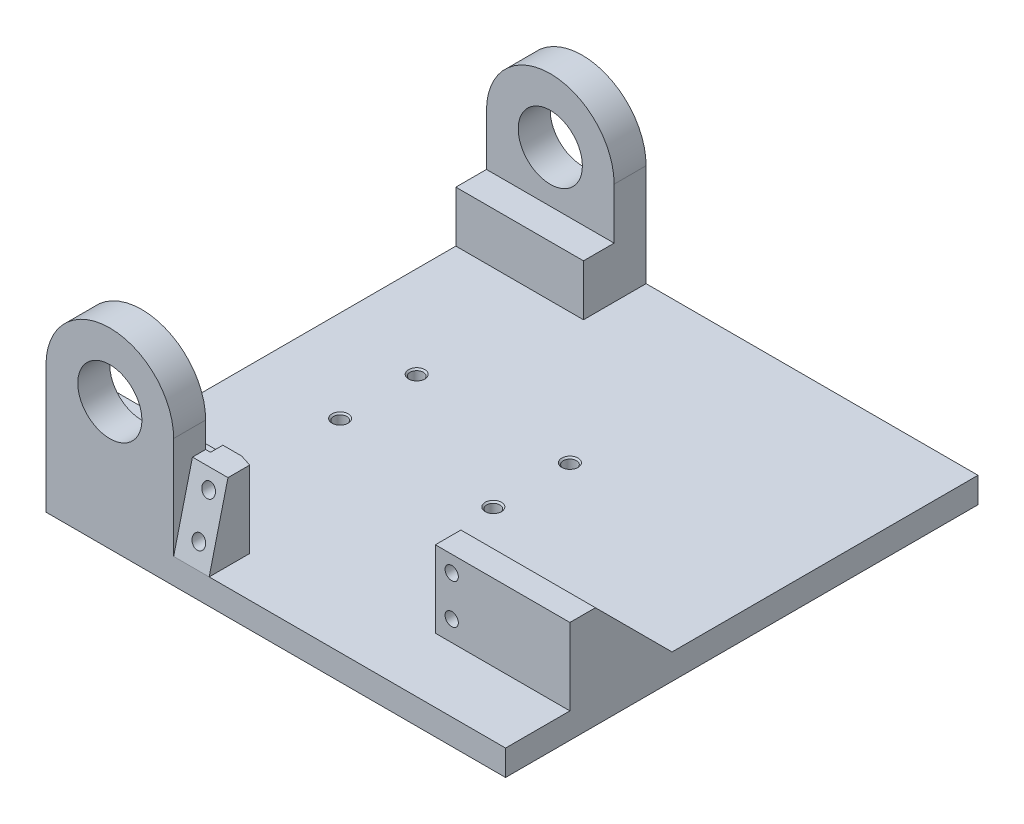
SolidWorks part; units mm, degrees
ref_plane "Front Plane" through (0, 0, 0) normal (0, 0, 1) x (1, 0, 0)
ref_plane "Top Plane" through (0, 0, 0) normal (0, 1, 0) x (1, 0, 0)
ref_plane "Right Plane" through (0, 0, 0) normal (1, 0, 0) x (0, 0, -1)
sketch "Sketch1" plane through (0, 0, 0) normal (0, 0, 1) x (1, 0, 0)
  line L0 (0, 0) -> (0, -38.1) construction
  line L1 (0, 0) -> (-38.1, 0) construction
  line L2 (0, 0) -> (38.1, 0) construction
  circle A0 centre (0, 0) radius 38.1 construction
  dimension "D1" = 76.2
  dimension "D2" = 90
  dimension "D3" = 90
sketch "Sketch2" plane through (0, 0, 0) normal (0, 0, 1) x (1, 0, 0)
  line L0 (0, -38.1) -> (0, 38.1) construction
  line L1 (-22.225, 0) -> (-22.225, -25.4)
  line L4 (-53.975, 0) -> (-53.975, -31.75)
  line L5 (-53.975, -31.75) -> (53.975, -31.75)
  line L9 (53.975, 0) -> (53.975, -31.75) construction
  line L10 (22.225, 0) -> (22.225, -25.4) construction
  line L11 (22.225, -25.4) -> (53.975, -25.4)
  line L12 (53.975, -25.4) -> (53.975, -31.75)
  line L13 (-22.225, -25.4) -> (22.225, -25.4)
  circle A0 centre (-38.1, 0) radius 7.9756
  arc A1 (-22.225, 0) -> (-53.975, 0) centre (-38.1, 0) ccw
  circle A2 centre (0, 0) radius 38.1 construction
  arc A5 (22.225, 0) -> (53.975, 0) centre (38.1, 0) cw construction
  circle A6 centre (38.1, 0) radius 7.9756 construction
  dimension "D1" = 15.9512
  dimension "D2" = 31.75
  dimension "D3" = 6.35
  dimension "D4" = 25.4
extrude "Boss-Extrude1" add sketch "Sketch2" along normal blind 7.9502 contours L1 L13 L12 L5 L4 A1
sketch "Sketch3" plane through (0, 0, 7.9502) normal (0, 0, 1) x (1, 0, 0)
  line L0 (53.975, -31.75) -> (53.975, -25.4) construction
  line L1 (-53.975, -31.75) -> (53.975, -31.75)
  line L2 (-53.975, -31.75) -> (-53.975, -25.4)
  line L3 (-53.975, -25.4) -> (53.975, -25.4)
  line L4 (53.975, -31.75) -> (53.975, -25.4)
  line L5 (53.975, -25.4) -> (-22.225, -25.4) construction
extrude "Boss-Extrude2" add sketch "Sketch3" along normal blind 101.6
sketch "Sketch4" plane through (0, 0, 109.5502) normal (0, 0, 1) x (1, 0, 0)
  line L0 (-53.975, 0) -> (-53.975, -31.75)
  line L1 (-53.975, -31.75) -> (53.975, -31.75)
  line L3 (-22.225, 0) -> (-22.225, -25.4)
  line L6 (-22.225, -25.4) -> (53.975, -25.4)
  line L7 (53.975, -25.4) -> (53.975, -31.75)
  circle A0 centre (-38.1, 0) radius 7.9756
  arc A1 (-22.225, 0) -> (-53.975, 0) centre (-38.1, 0) ccw
  circle A4 centre (-38.1, 0) radius 7.9756 construction
  dimension "D1" = 15.9512
extrude "Boss-Extrude3" add sketch "Sketch4" along normal blind 7.9502
sketch "Sketch5" plane through (53.975, 0, 0) normal (1, 0, 0) x (0, 0, -1)
  line L1 (0, -31.75) -> (-117.5004, -31.75)
  line L2 (0, -31.75) -> (0, -25.4)
  line L3 (0, -25.4) -> (-117.5004, -25.4)
  line L4 (-117.5004, -31.75) -> (-117.5004, -25.4)
extrude "Boss-Extrude4" add sketch "Sketch5" along normal blind 6.35
sketch "Sketch6" plane through (0, -25.4, 0) normal (0, 1, 0) x (1, 0, 0)
  line L0 (60.325, 0) -> (60.325, -117.5004) construction
  line L1 (60.325, -101.4984) -> (26.8617, -101.4984)
  line L2 (60.325, -101.4984) -> (60.325, -95.1484)
  line L3 (60.325, -95.1484) -> (26.8617, -95.1484)
  line L4 (26.8617, -101.4984) -> (26.8617, -95.1484)
  line L5 (26.8617, -102.4002) -> (26.8617, -74.9502) construction
  line L6 (60.325, -117.5004) -> (-22.225, -117.5004) construction
  line L7 (-20.2383, -106.4752) -> (-14.2383, -106.4752) construction
  line L9 (-13.3923, -112.8252) -> (-13.3923, -107.4183)
  line L10 (-16.3298, -106.4752) -> (-21.0123, -106.4752)
  line L12 (-13.1383, -105.5502) -> (-13.1383, -113.7002) construction
  line L13 (-21.0123, -106.4752) -> (-21.0123, -109.5502)
  line L14 (-22.225, -109.5502) -> (-53.975, -109.5502) construction
  line L15 (-21.0123, -109.5502) -> (-22.225, -109.5502)
  line L16 (-22.225, -109.5502) -> (-22.225, -112.8252)
  line L17 (-22.225, -117.5004) -> (-22.225, -109.5502) construction
  line L18 (-22.225, -112.8252) -> (-13.3923, -112.8252)
  line L19 (-16.3298, -106.4752) -> (-13.3923, -107.4183)
  line L21 (-19.1883, -105.5502) -> (-13.1383, -107.5002) construction
  dimension "D1" = 16.002
  dimension "D2" = 6.35
  dimension "D3" = 0
  dimension "D4" = 0.254
  dimension "D5" = 6.35
  dimension "D6" = 7.62
  dimension "D7" = 17.8
extrude "Boss-Extrude5" add sketch "Sketch6" along normal blind 19.05
sketch "Sketch8" plane through (60.325, 0, 0) normal (1, 0, 0) x (0, 0, -1)
  line L0 (-95.1484, -6.35) -> (-76.0984, -25.4)
  line L1 (0, -25.4) -> (-95.1484, -25.4) construction
  line L2 (-76.0984, -25.4) -> (-95.1484, -25.4)
  line L3 (-95.1484, -25.4) -> (-95.1484, -6.35)
  dimension "D1" = 45
extrude "Boss-Extrude6" add sketch "Sketch8" against normal up to vertex
sketch "Sketch10" plane through (-22.225, 0, 0) normal (1, 0, 0) x (0, 0, -1)
  line L0 (-112.8252, -6.35) -> (-117.5004, -25.4)
  line L1 (-117.5004, -25.4) -> (-112.8252, -25.4)
  line L2 (-112.8252, -25.4) -> (-112.8252, -6.35)
extrude "Boss-Extrude8" add sketch "Sketch10" along normal up to vertex
sketch "Sketch11" plane through (0, -25.4, 0) normal (0, 1, 0) x (1, 0, 0)
  line L0 (-31.2237, -48.0502) -> (6.8763, -48.0502) construction
  line L1 (-18.5237, -9.9502) -> (-5.8237, -9.9502) construction
  line L2 (-12.1737, 2.7498) -> (-12.1737, -48.0502) construction
  point P0 (-31.2237, -67.1002)
  point P1 (-31.2237, -48.0502)
  point P2 (6.8763, -67.1002)
  point P3 (6.8763, -48.0502)
  point P6 (-12.1737, -48.0502)
  point P11 (-12.1737, -9.9502)
  dimension "D1" = 19.05
  dimension "D2" = 19.05
  dimension "D3" = 38.1
  dimension "D4" = 50.8
hole_wizard "M4x0.7 Tapped Hole1" positions "Sketch14" profile "Sketch13" tap size "M4x0.7" standard "ANSI Metric" end condition through all
sketch "Sketch14" plane through (0, -25.4, 0) normal (0, 1, 0) x (1, 0, 0)
  point P0 (6.8763, -48.0502)
  point P3 (6.8763, -67.1002)
  point P6 (-31.2237, -67.1002)
  point P9 (-31.2237, -48.0502)
sketch "Sketch13" plane through (6.8763, -25.4, 48.0502) normal (1, 0, 0) x (0, 0, 1)
  line L0 (0, 0) -> (0, 6.35)
  line L1 (0, 6.35) -> (1.65, 6.35)
  line L2 (1.65, 6.35) -> (1.65, 0.375)
  line L3 (1.65, 0.375) -> (2.025, 0)
  line L5 (2.025, 0) -> (0, 0)
  line L6 (-1.65, 0.375) -> (-2.025, 0) construction
  line L11 (0, -6.35) -> (0, 107.95) construction
  dimension "Thru Tap Drill Dia." = 3.3
  dimension "Thru Tap Drill Depth" = 6.35
  dimension "Near C'Sink Dia." = 4.05
  dimension "Near C'Sink Angle" = 90
cosmetic thread "Hole Thread3" parameters "D2"=4
cosmetic thread "Hole Thread4" parameters "D2"=4
cosmetic thread "Hole Thread5" parameters "D2"=4
cosmetic thread "Hole Thread6" parameters "D2"=4
sketch "Sketch15" plane through (0, 0, 101.4984) normal (0, 0, 1) x (1, 0, 0)
  line L0 (26.8617, -6.35) -> (26.8617, -25.4) construction
  line L1 (26.8617, -6.35) -> (60.325, -6.35) construction
  circle A0 centre (30.9257, -10.414) radius 1.651
  circle A1 centre (30.9257, -20.32) radius 1.651
  dimension "D1" = 3.302
  dimension "D2" = 9.906
  dimension "D3" = 4.064
  dimension "D4" = 4.064
extrude "Cut-Extrude1" cut sketch "Sketch15" against normal up to next
sketch "Sketch18" plane through (0, 0, 106.4752) normal (0, 0, -1) x (-1, 0, 0)
  line L0 (16.3298, -6.35) -> (21.0123, -6.35) construction
  line L2 (21.0123, -6.35) -> (21.0123, -25.4) construction
  circle A0 centre (17.2023, -10.414) radius 1.651
  circle A1 centre (17.2023, -20.32) radius 1.651
  dimension "D1" = 3.302
  dimension "D2" = 4.064
  dimension "D3" = 3.81
  dimension "D4" = 9.906
extrude "Cut-Extrude2" cut sketch "Sketch18" against normal up to next
sketch "Sketch19" plane through (-53.975, 0, 0) normal (-1, 0, 0) x (0, 0, 1)
  line L0 (7.9502, -12.7) -> (15.5702, -12.7)
  line L1 (7.9502, 0) -> (7.9502, -25.4) construction
  line L2 (15.5702, -12.7) -> (15.5702, -25.4)
  line L4 (109.5502, -12.7) -> (101.9302, -12.7)
  line L5 (109.5502, 0) -> (109.5502, -25.4) construction
  line L6 (101.9302, -12.7) -> (101.9302, -25.4)
  line L7 (109.5502, -25.4) -> (7.9502, -25.4) construction
  line L8 (7.9502, -12.7) -> (7.9502, -25.4)
  line L9 (7.9502, -25.4) -> (15.5702, -25.4)
  line L10 (109.5502, -12.7) -> (109.5502, -25.4)
  line L11 (109.5502, -25.4) -> (101.9302, -25.4)
  line L12 (-2.7498, -25.4) -> (48.0502, -25.4) construction
  dimension "D1" = 7.62
  dimension "D2" = 7.62
extrude "Boss-Extrude9" add sketch "Sketch19" against normal up to vertex
